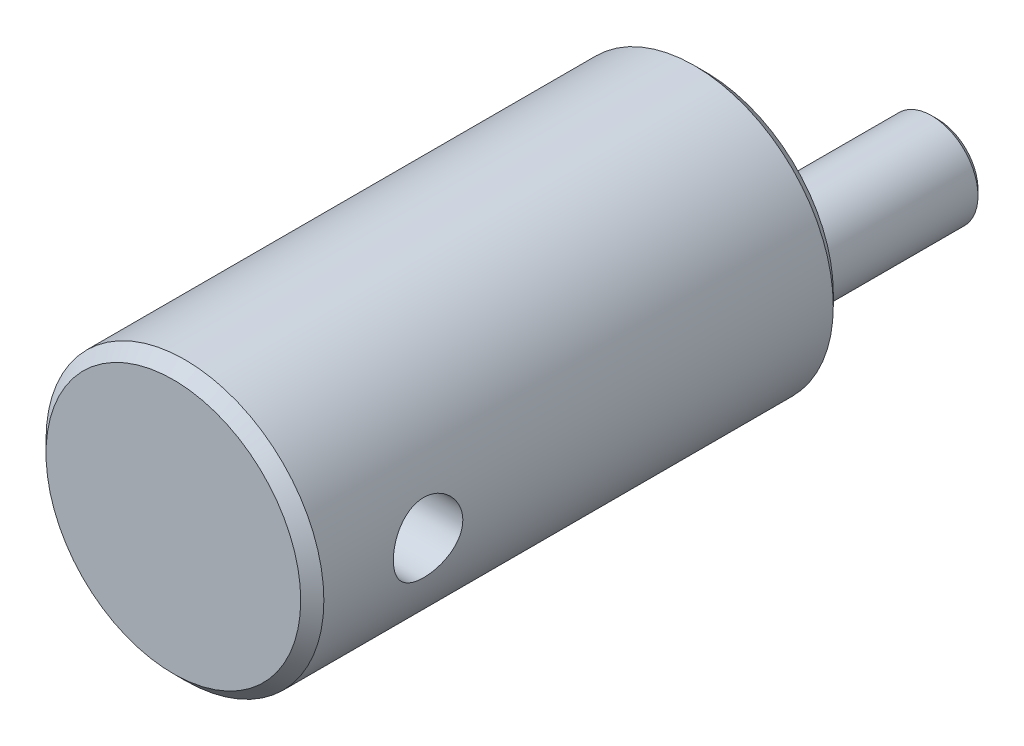
SolidWorks part; units mm, degrees
ref_plane "Front Plane" through (0, 0, 0) normal (0, 0, 1) x (1, 0, 0)
ref_plane "Top Plane" through (0, 0, 0) normal (0, 1, 0) x (1, 0, 0)
ref_plane "Right Plane" through (0, 0, 0) normal (1, 0, 0) x (0, 0, -1)
sketch "Sketch1" plane through (0, 0, 0) normal (0, 0, 1) x (1, 0, 0)
  circle A0 centre (0, 0) radius 6
  dimension "D1" = 12
extrude "Boss-Extrude1" add sketch "Sketch1" along normal blind 23
chamfer "Chamfer1" distance 0.5 angle 45 2 edges at (6, 0, 0) (6, 0, 23)
sketch "Sketch2" plane through (0, 0, 0) normal (0, 0, -1) x (-1, 0, 0)
  circle A0 centre (0, -3) radius 2
  dimension "D1" = 4
  dimension "D2" = 3
extrude "Boss-Extrude2" add sketch "Sketch2" along normal blind 10
chamfer "Chamfer2" distance 0.25 angle 45 1 edges at (-2, -3, -10)
sketch "Sketch3" plane through (0, 0, 0) normal (1, 0, 0) x (0, 0, -1)
  line L0 (-23, 5.5) -> (-23, -5.5) construction
  circle A0 centre (-18, 0) radius 1.5
  dimension "D1" = 3
  dimension "D2" = 5
extrude "Cut-Extrude1" cut sketch "Sketch3" against normal through all both and the other way through all
